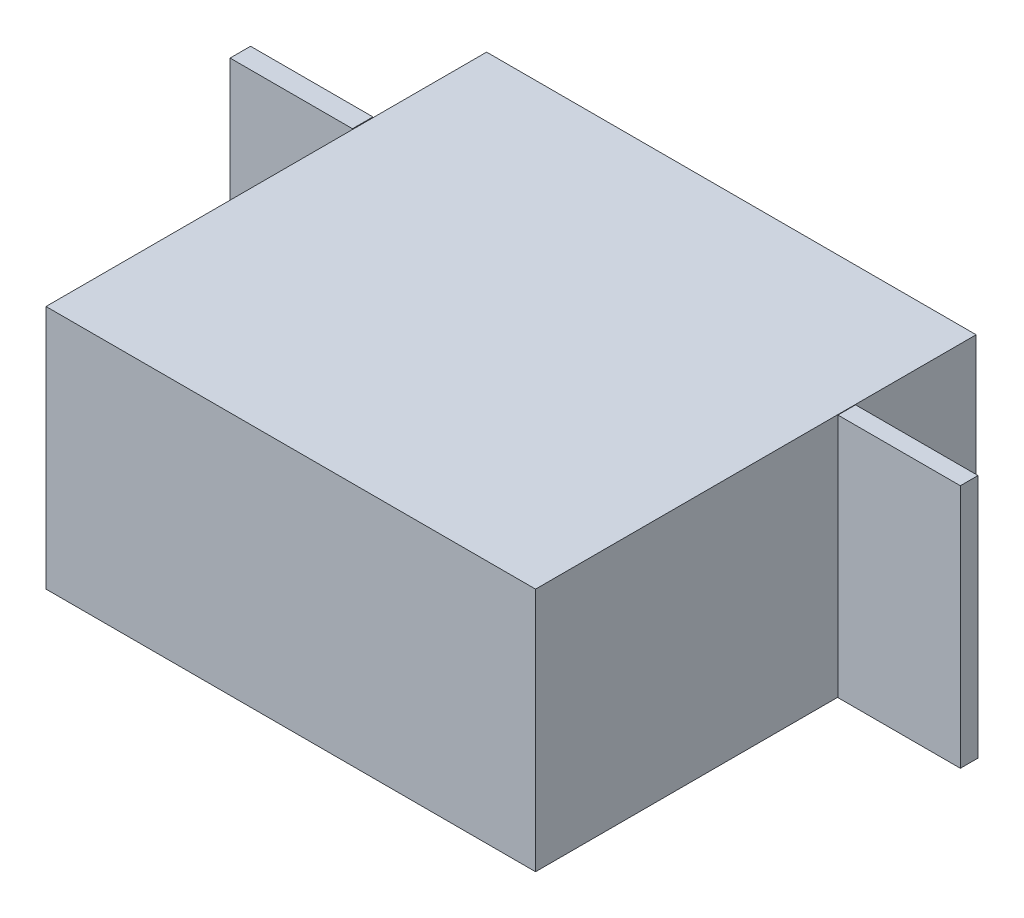
SolidWorks part; units mm, degrees
ref_plane "Front Plane" through (0, 0, 0) normal (0, 0, 1) x (1, 0, 0)
ref_plane "Top Plane" through (0, 0, 0) normal (0, 1, 0) x (1, 0, 0)
ref_plane "Right Plane" through (0, 0, 0) normal (1, 0, 0) x (0, 0, -1)
sketch "草图1" plane through (0, 0, 0) normal (0, 0, 1) x (1, 0, 0)
  line L1 (-365.4035, -231.7719) -> (-325.4035, -231.7719)
  line L2 (-365.4035, -231.7719) -> (-365.4035, -251.7719)
  line L3 (-365.4035, -251.7719) -> (-325.4035, -251.7719)
  line L4 (-325.4035, -231.7719) -> (-325.4035, -251.7719)
  dimension "D1" = 20
  dimension "D2" = 40
extrude "凸台-拉伸1" add sketch "草图1" against normal blind 36
sketch "草图2" plane through (-365.4035, 0, -0.002) normal (-1, 0, 0) x (0, 0, 1)
  line L1 (-26.7118, -251.7141) -> (-25.04, -251.7141)
  line L2 (-26.7118, -251.7141) -> (-26.7118, -231.7141)
  line L3 (-26.7118, -231.7141) -> (-25.04, -231.7141)
  line L4 (-25.04, -251.7141) -> (-25.04, -231.7141)
  dimension "D1" = 20
extrude "凸台-拉伸2" add sketch "草图2" along normal blind 10
sketch "草图5" plane through (-325.4035, 0, -0.7529) normal (1, 0, 0) x (0, 0, -1)
  line L1 (23.9556, -251.8055) -> (25.398, -251.8055)
  line L2 (23.9556, -251.8055) -> (23.9556, -231.8095)
  line L3 (23.9556, -231.8095) -> (25.398, -231.8095)
  line L4 (25.398, -251.8055) -> (25.398, -231.8095)
  dimension "D1" = 19.996
extrude "凸台-拉伸5" add sketch "草图5" along normal blind 10
sketch "草图7" plane through (-2.2262, -0.8402, -36) normal (0, 0, -1) x (-1, 0, 0)
  circle A0 centre (333.3084, -240.7494) radius 6.5
  dimension "D1" = 13
extrude "凸台-拉伸6" add sketch "草图7" along normal blind 2
